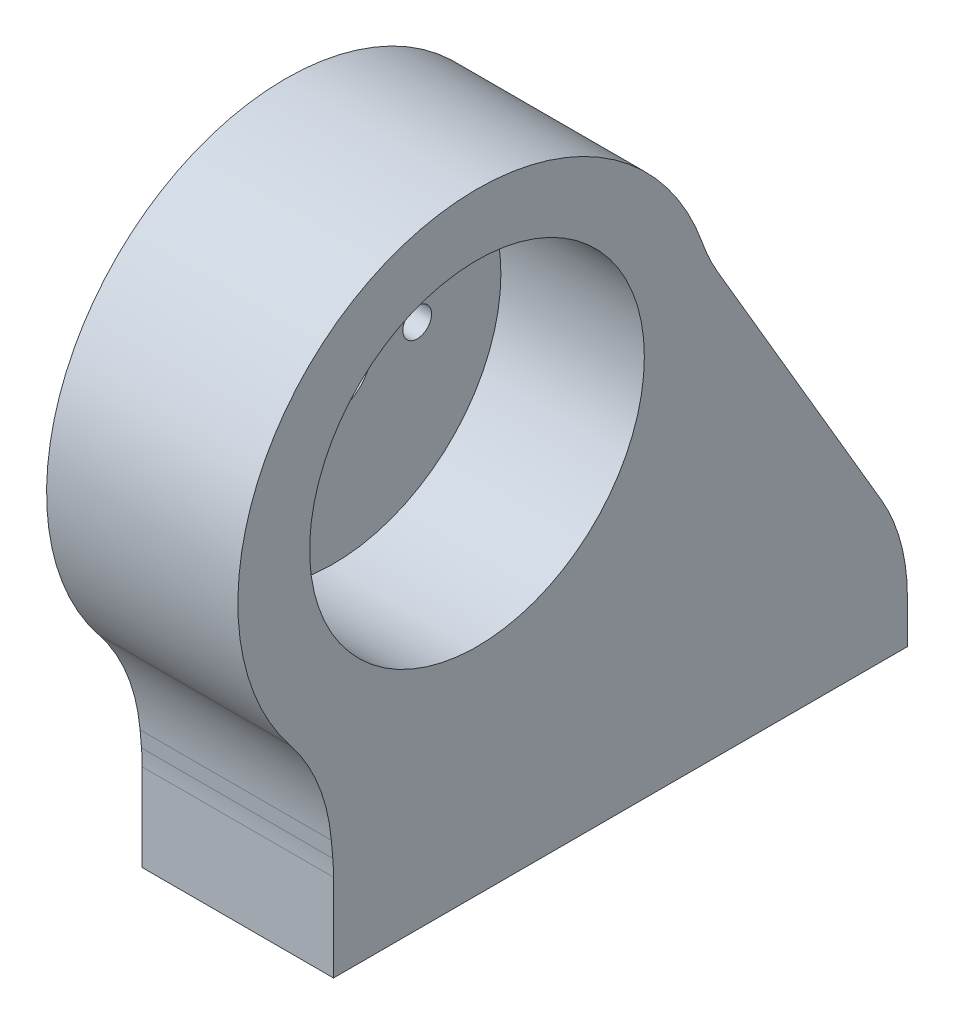
SolidWorks part; units mm, degrees
ref_plane "Alzado" through (0, 0, 0) normal (0, 0, 1) x (1, 0, 0)
ref_plane "Planta" through (0, 0, 0) normal (0, 1, 0) x (1, 0, 0)
ref_plane "Vista lateral" through (0, 0, 0) normal (1, 0, 0) x (0, 0, -1)
sketch "Croquis3" plane through (0, 0, 0) normal (1, 0, 0) x (0, 0, -1)
  line L0 (27.2556, 9.6834) -> (10.1616, 38.8542)
  line L1 (30, -5) -> (-30, -5)
  line L2 (30, -5) -> (30, -0.4283)
  line L4 (-30, -5) -> (-30, 4.1266)
  line L5 (30, -5) -> (-30, 5) construction
  line L6 (30, 5) -> (-30, -5) construction
  line L7 (-30.0761, 5.8701) -> (-30.2263, 7.5859)
  arc A0 (8.5651, 42.2876) -> (-34.5279, 18.3301) centre (-15, 33.9398) ccw
  arc A1 (30, -0.4283) -> (27.2556, 9.6834) centre (10, -0.4283) ccw
  arc A2 (-30, 4.1266) -> (-30.0761, 5.8701) centre (-50, 4.1266) ccw
  arc A3 (-30.2263, 7.5859) -> (-34.5279, 18.3301) centre (-50.1501, 5.8424) ccw
  arc A4 (10.1616, 38.8542) -> (8.5651, 42.2876) centre (27.4172, 48.9658) cw
  point P0 (0, 0)
  dimension "D3" = 50
  dimension "D2" = 20
  dimension "D1" = 60
  dimension "D4" = 15
  dimension "D5" = 10
extrude "Saliente-Extruir1" add sketch "Croquis3" against normal blind 20
sketch "Croquis5" plane through (0, 0, 0) normal (1, 0, 0) x (0, 0, -1)
  line L0 (-30, -5) -> (30, -5) construction
  circle A0 centre (-15, 35) radius 17.5
  dimension "D2" = 35
  dimension "D1" = 15
  dimension "D3" = 40
extrude "Cortar-Extruir1" cut sketch "Croquis5" against normal blind 15
sketch "Croquis6" plane through (-15, 0, 0) normal (1, 0, 0) x (0, 0, -1)
  circle A0 centre (-15, 35) radius 4
  circle A1 centre (-6.25, 35) radius 1.5
  circle A2 centre (-23.75, 35) radius 1.5
  dimension "D1" = 8
  dimension "D2" = 3
  dimension "D3" = 17.5
  dimension "D4" = 8.75
extrude "Cortar-Extruir2" cut sketch "Croquis6" against normal blind 6
sketch "Croquis7" plane through (-20, 0, 0) normal (-1, 0, 0) x (0, 0, 1)
  circle A0 centre (6.25, 35) radius 3
  circle A1 centre (23.75, 35) radius 3
  dimension "D1" = 6
extrude "Cortar-Extruir3" cut sketch "Croquis7" against normal blind 2
